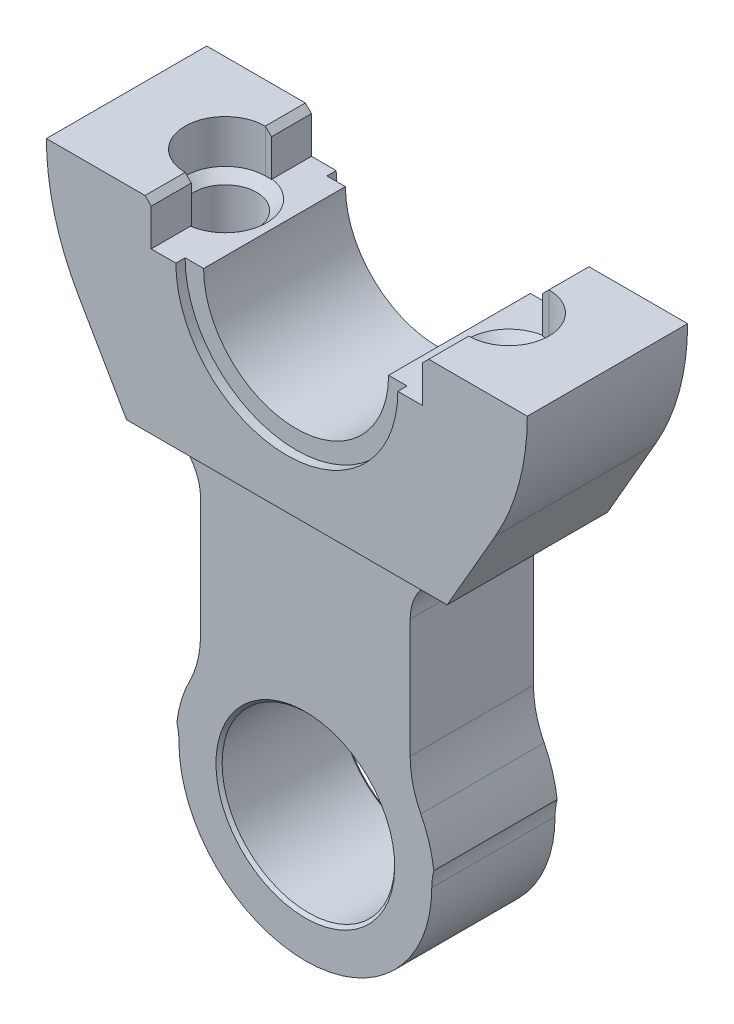
SolidWorks part; units mm, degrees
material "Сталь 20 ГОСТ 1050-2013"
ref_plane "Спереди" through (0, 0, 0) normal (0, 0, 1) x (1, 0, 0)
ref_plane "Сверху" through (0, 0, 0) normal (0, 1, 0) x (1, 0, 0)
ref_plane "Справа" through (0, 0, 0) normal (1, 0, 0) x (0, 0, -1)
other "Таблица"
sketch "Эскиз1" plane through (0, 0, 0) normal (0, 0, 1) x (1, 0, 0)
  line L0 (0, -128.6383) -> (0, 22.4317) construction
  line L1 (33.7958, -19.4639) -> (26, -33)
  line L2 (26, -33) -> (25, -33)
  line L3 (17, -41) -> (17, -60.2668)
  line L4 (-17, -41) -> (-17, -60.2668)
  line L5 (-26, -33) -> (-25, -33)
  line L6 (-33.7958, -19.4639) -> (-26, -33)
  line L7 (39, 0) -> (22, 0)
  line L8 (-75.2542, 0) -> (75.2542, 0) construction
  line L9 (22, 0) -> (22, -7)
  line L10 (-22, -7) -> (-15, -7)
  line L11 (22, -7) -> (15, -7)
  line L12 (-22, -7) -> (-22, 0)
  line L13 (-22, 0) -> (-39, 0)
  arc A0 (-39, 0) -> (-33.7958, -19.4639) centre (0, 0) ccw
  arc A1 (17, -60.2668) -> (18.7297, -67.5028) centre (33, -60.2668) ccw
  arc A2 (18.7297, -67.5028) -> (20.8402, -74.414) centre (0, -77) cw
  arc A3 (20.8402, -74.414) -> (20.5, -77) centre (30.5, -77) ccw
  arc A4 (20.5, -77) -> (-20.5, -77) centre (0, -77) cw
  arc A5 (-20.8402, -74.414) -> (-20.5, -77) centre (-30.5, -77) cw
  arc A6 (33.7958, -19.4639) -> (39, 0) centre (0, 0) ccw
  arc A7 (-18.7297, -67.5028) -> (-20.8402, -74.414) centre (0, -77) ccw
  arc A8 (-17, -60.2668) -> (-18.7297, -67.5028) centre (-33, -60.2668) cw
  arc A9 (15, -7) -> (-15, -7) centre (0, -7) cw
  circle A10 centre (0, -77) radius 14
  arc A11 (25, -33) -> (17, -41) centre (25, -41) ccw
  arc A12 (-17, -41) -> (-25, -33) centre (-25, -41) ccw
  point P28 (0, 0)
  point P39 (17, -33)
  point P42 (-17, -33)
  dimension "D5" = 16
  dimension "D6" = 10
  dimension "D7" = 21
  dimension "D8" = 20.5
  dimension "D9" = 44
  dimension "D10" = 15
  dimension "D13" = 28
  dimension "D15" = 8
  dimension "D14" = 39
  dimension "D2" = 33
  dimension "D3" = 52
  dimension "D4" = 34
  dimension "D11" = 7
  dimension "D12" = 70
extrude "Бобышка-Вытянуть1" add sketch "Эскиз1" along normal mid plane 26
sketch "Эскиз2" plane through (0, 0, 0) normal (1, 0, 0) x (0, 0, -1)
  line L0 (0, 17.4918) -> (0, -107.1669) construction
  line L1 (13, 0) -> (-13, 0)
  line L2 (-13, -97.5) -> (13, -97.5) construction
  line L3 (10, -97.5) -> (10, -34.6)
  line L4 (11.6, -33) -> (13, -33)
  line L5 (13, -33) -> (13, -19.4639) construction
  line L6 (13, -33) -> (13, 0)
  line L7 (-13, 0) -> (-13, -33)
  line L8 (-11.6, -33) -> (-13, -33)
  line L9 (-10, -97.5) -> (-10, -34.6)
  line L10 (-10, -97.5) -> (10, -97.5)
  line L11 (-13, -33) -> (13, -33) construction
  arc A0 (11.6, -33) -> (10, -34.6) centre (11.6, -34.6) ccw
  arc A1 (-11.6, -33) -> (-10, -34.6) centre (-11.6, -34.6) cw
  dimension "D1" = 1.6
  dimension "D3" = 20
extrude "Вырез-Вытянуть1" cut sketch "Эскиз2" against normal through all and the other way through all flip side to cut
sketch "Эскиз3" plane through (0, 0, 0) normal (0, 1, 0) x (1, 0, 0)
  line L0 (-43.1962, 0) -> (42.0701, 0) construction
  line L1 (0, -22.5634) -> (0, 18.8632) construction
  line L2 (23, 6.5) -> (22, 6.5)
  line L3 (22, -13) -> (22, 13) construction
  line L4 (23, -6.5) -> (22, -6.5)
  line L5 (22, 6.5) -> (22, -6.5)
  line L6 (-22, 6.5) -> (-22, -6.5)
  line L7 (-23, -6.5) -> (-22, -6.5)
  line L8 (-23, 6.5) -> (-22, 6.5)
  arc A0 (23, -6.5) -> (23, 6.5) centre (23, 0) ccw
  arc A1 (-23, -6.5) -> (-23, 6.5) centre (-23, 0) cw
  dimension "D1" = 6.5
  dimension "D2" = 46
extrude "Вырез-Вытянуть2" cut sketch "Эскиз3" against normal up to surface (7 mm away) up to face at (-18.5, -7, 0)
chamfer "Фаска1" distance 1 angle 45 4 edges at (22, 0, -9.75) (22, 0, 9.75) (-22, 0, 9.75) (-22, 0, -9.75)
chamfer "Фаска2" distance 0.5 angle 45 2 edges at (-14, -77, -10) (0, -91, 10)
sketch "Эскиз4" plane through (0, 0, 13) normal (0, 0, 1) x (1, 0, 0)
  line L0 (0, 3.7548) -> (0, -38.5353) construction
  circle A0 centre (0, -7) radius 18
  arc A3 (-15, -7) -> (15, -7) centre (0, -7) ccw construction
  arc A4 (-15, -7) -> (15, -7) centre (0, -7) ccw construction
  dimension "D1" = 36
extrude "Вырез-Вытянуть3" cut sketch "Эскиз4" against normal blind 1.5
mirror "Зеркальное отражение1" about plane through (0, 0, 0) normal (0, 0, 1) of "Вырез-Вытянуть3"
hole_wizard "Отверстие обработанное метчиком M121" positions "Эскиз7" profile "Эскиз6" tap size "M12" standard "ISO"
sketch "Эскиз7" plane through (0, -7, 0) normal (0, 1, 0) x (1, 0, 0)
  point P0 (-23, 0)
  point P2 (23, 0)
sketch "Эскиз6" plane through (-23, -7, 0) normal (1, 0, 0) x (0, 0, 1)
  line L0 (0, 0) -> (0, 19.9445)
  line L1 (0, 19.9445) -> (5.1, 17)
  line L2 (5.1, 17) -> (5.1, 1.6)
  line L3 (5.1, 1.6) -> (6.7, 0)
  line L5 (6.7, 0) -> (0, 0)
  line L6 (-5.1, 1.6) -> (-6.7, 0) construction
  line L10 (0, 19.9445) -> (-5.1, 17) construction
  line L11 (0, -6.35) -> (0, 107.95) construction
  dimension "Диаметр сверла" = 10.2
  dimension "Глубина сверла" = 17
  dimension "Диаметр передней зенковки" = 13.4
  dimension "Угол передней зенковки" = 90
  dimension "Угол заточки сверла" = 120
cosmetic thread "Отверстие резьбы3" parameters "D1"=12, "D2"=12
cosmetic thread "Отверстие резьбы4" parameters "D1"=12, "D2"=12
